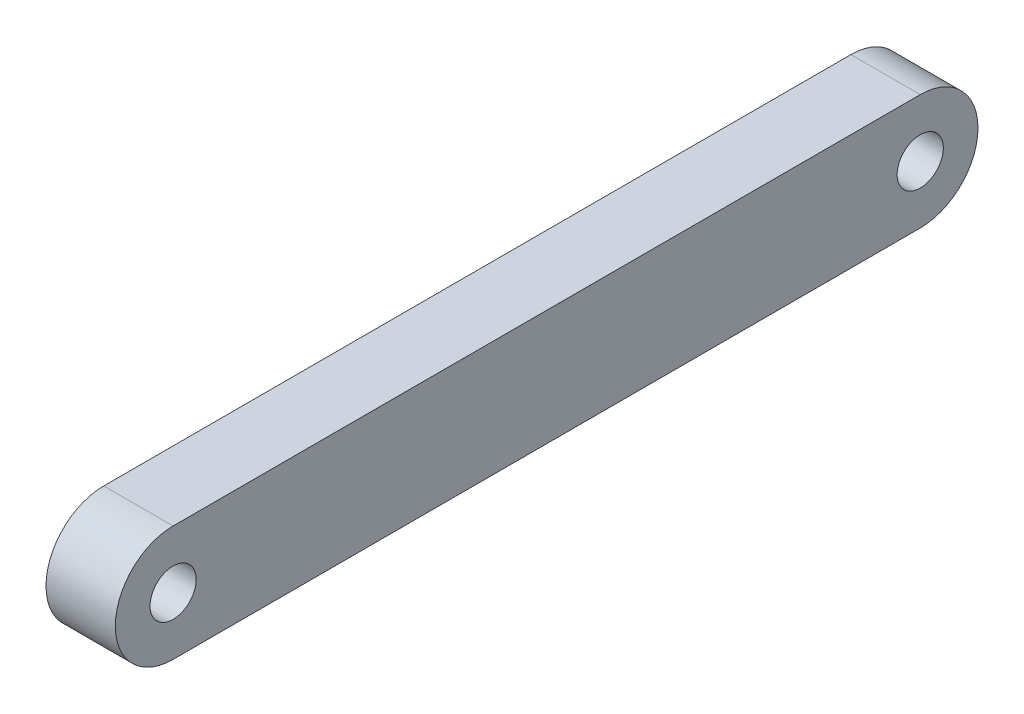
SolidWorks part; units mm, degrees
material "ABS P400"
ref_plane "Front Plane" through (0, 0, 0) normal (0, 0, 1) x (1, 0, 0)
ref_plane "Top Plane" through (0, 0, 0) normal (0, 1, 0) x (1, 0, 0)
ref_plane "Right Plane" through (0, 0, 0) normal (1, 0, 0) x (0, 0, -1)
sketch "Sketch1" plane through (0, 0, 0) normal (1, 0, 0) x (0, 0, -1)
  line L0 (-32.325, 0) -> (32.325, 0) construction
  line L1 (-32.325, 5) -> (32.325, 5)
  line L2 (-32.325, -5) -> (32.325, -5)
  arc A0 (-32.325, 5) -> (-32.325, -5) centre (-32.325, 0) ccw
  arc A1 (32.325, -5) -> (32.325, 5) centre (32.325, 0) ccw
  circle A2 centre (-32.325, 0) radius 2
  circle A3 centre (32.325, 0) radius 2
  point P2 (0, 0)
  dimension "D2" = 4
  dimension "D3" = 4
  dimension "D1" = 64.65
  dimension "D4" = 10
extrude "Boss-Extrude1" add sketch "Sketch1" along normal mid plane 6
